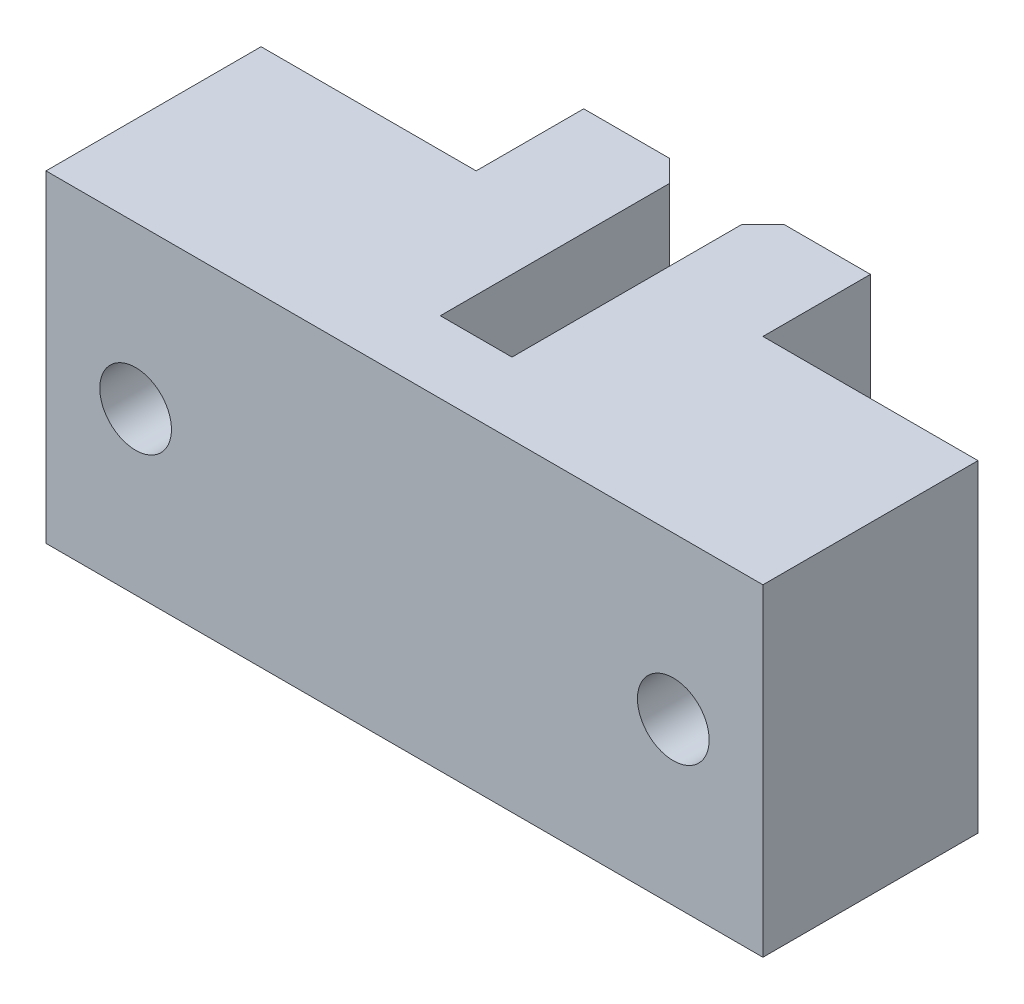
SolidWorks part; units mm, degrees
ref_plane "Спереди" through (0, 0, 0) normal (0, 0, 1) x (1, 0, 0)
ref_plane "Сверху" through (0, 0, 0) normal (0, 1, 0) x (1, 0, 0)
ref_plane "Справа" through (0, 0, 0) normal (1, 0, 0) x (0, 0, -1)
sketch "Эскиз1" plane through (0, 0, 0) normal (0, 1, 0) x (1, 0, 0)
  line L0 (-794.818, 0) -> (38946.0809, 0) construction
  line L1 (0, -794.818) -> (0, 38946.0809) construction
  line L2 (50, 0) -> (-50, 0)
  line L3 (-50, 0) -> (-50, 30)
  line L4 (-50, 30) -> (-20, 30)
  line L5 (-20, 30) -> (-20, 45)
  line L6 (-20, 45) -> (-8, 45)
  line L7 (-8, 45) -> (-5, 42)
  line L8 (-5, 42) -> (-5, 10)
  line L9 (-5, 10) -> (5, 10)
  line L10 (5, 42) -> (5, 10)
  line L11 (8, 45) -> (5, 42)
  line L12 (20, 45) -> (8, 45)
  line L13 (20, 30) -> (20, 45)
  line L14 (50, 30) -> (20, 30)
  line L15 (50, 0) -> (50, 30)
  point P15 (0, 10)
  point P21 (0, 0)
  dimension "D1" = 10
  dimension "D2" = 40
  dimension "D3" = 100
  dimension "D4" = 3
  dimension "D5" = 45
  dimension "D6" = 45
  dimension "D7" = 30
  dimension "D8" = 35
extrude "Бобышка-Вытянуть1" add sketch "Эскиз1" along normal mid plane 45
sketch "Эскиз2" plane through (0, 0, -30) normal (0, 0, -1) x (-1, 0, 0)
  line L0 (-1000, 0) -> (49000, 0) construction
  line L1 (50, 22.5) -> (50, -22.5) construction
  circle A0 centre (37.5, 0) radius 8
  dimension "D2" = 16
  dimension "D1" = 12.5
extrude "Вырез-Вытянуть1" cut sketch "Эскиз2" against normal blind 10
sketch "Эскиз3" plane through (0, 0, -20) normal (0, 0, -1) x (-1, 0, 0)
  circle A0 centre (37.5, 0) radius 5
  dimension "D1" = 10
extrude "Вырез-Вытянуть2" cut sketch "Эскиз3" against normal up to next
mirror "Зеркальное отражение1" about plane through (0, 0, 0) normal (1, 0, 0) of "Вырез-Вытянуть2", "Вырез-Вытянуть1"
